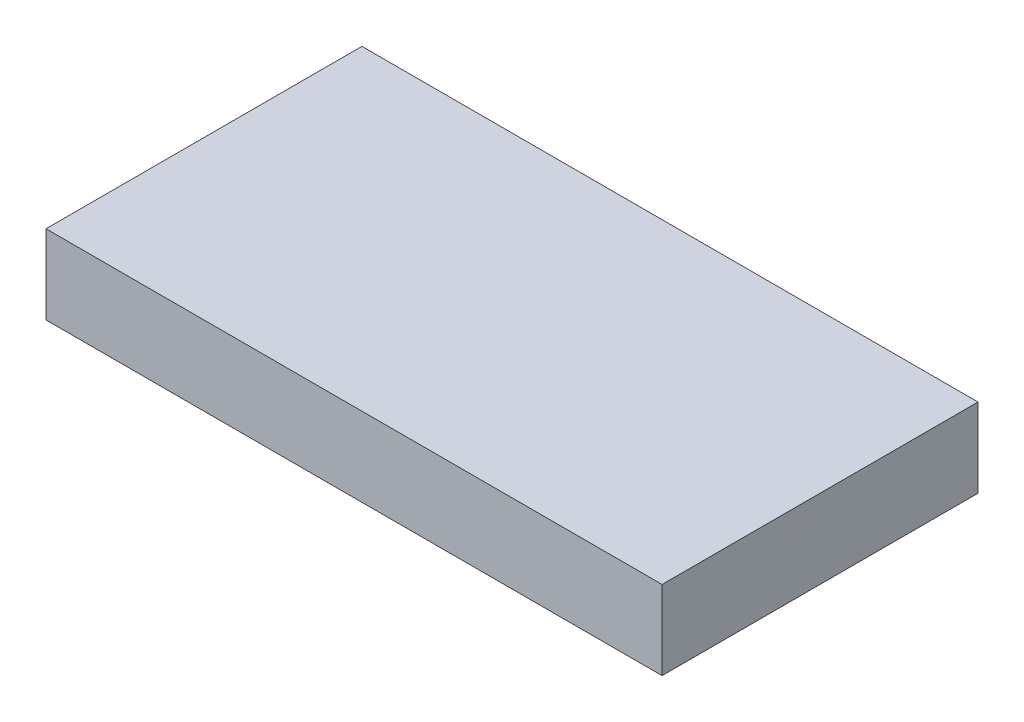
SolidWorks part; units mm, degrees
ref_plane "Front Plane" through (0, 0, 0) normal (0, 0, 1) x (1, 0, 0)
ref_plane "Top Plane" through (0, 0, 0) normal (0, 1, 0) x (1, 0, 0)
ref_plane "Right Plane" through (0, 0, 0) normal (1, 0, 0) x (0, 0, -1)
sketch "Sketch1" plane through (0, 0, 0) normal (0, 0, 1) x (1, 0, 0)
  line L1 (0, 0) -> (39, 0)
  line L2 (0, 0) -> (0, 5)
  line L3 (0, 5) -> (39, 5)
  line L4 (39, 0) -> (39, 5)
extrude "Boss-Extrude1" add sketch "Sketch1" along normal blind 20
